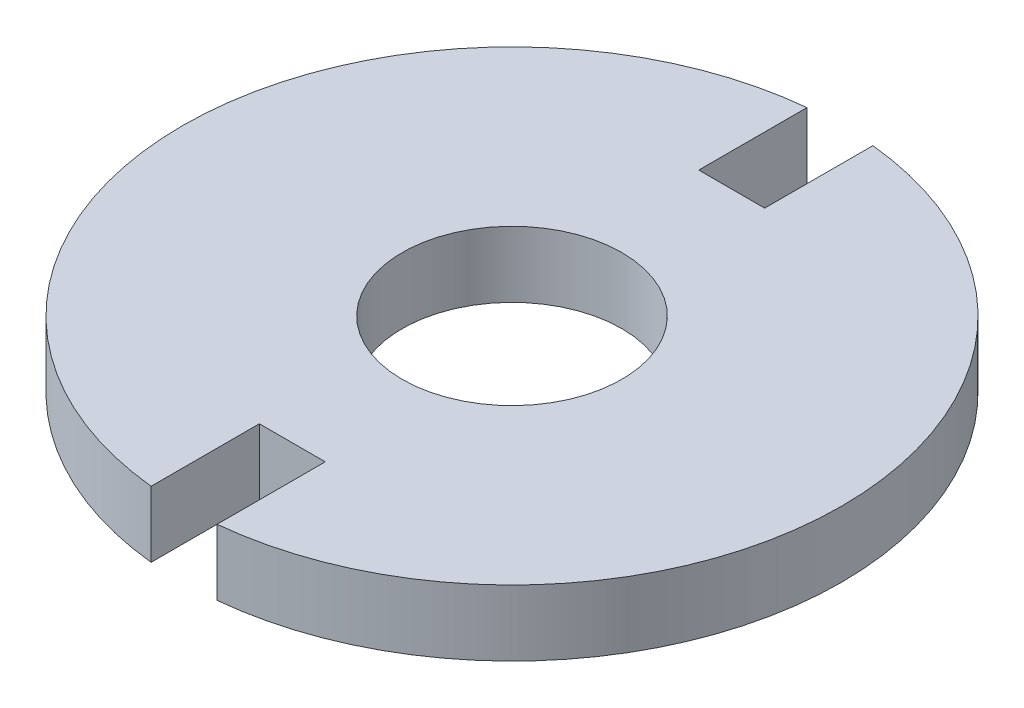
SolidWorks part; units mm, degrees
ref_plane "前视基准面" through (0, 0, 0) normal (0, 0, 1) x (1, 0, 0)
ref_plane "上视基准面" through (0, 0, 0) normal (0, 1, 0) x (1, 0, 0)
ref_plane "右视基准面" through (0, 0, 0) normal (1, 0, 0) x (0, 0, -1)
sketch "草图1" plane through (0, 0, 0) normal (0, 1, 0) x (1, 0, 0)
  line L2 (-1.5, -14.9248) -> (-1.5, -10)
  line L4 (1.5, -14.9248) -> (1.5, -10)
  line L7 (-1.5, -10) -> (1.5, -10)
  line L9 (-1.5, 10) -> (1.5, 10)
  line L14 (-1.5, 10) -> (-1.5, 14.9248)
  line L17 (1.5, 10) -> (1.5, 14.9248)
  circle A0 centre (0, 0) radius 5
  arc A1 (1.5, -14.9248) -> (1.5, 14.9248) centre (0, 0) ccw
  arc A2 (-1.5, 14.9248) -> (-1.5, -14.9248) centre (0, 0) ccw
extrude "凸台-拉伸1" add sketch "草图1" along normal blind 3
